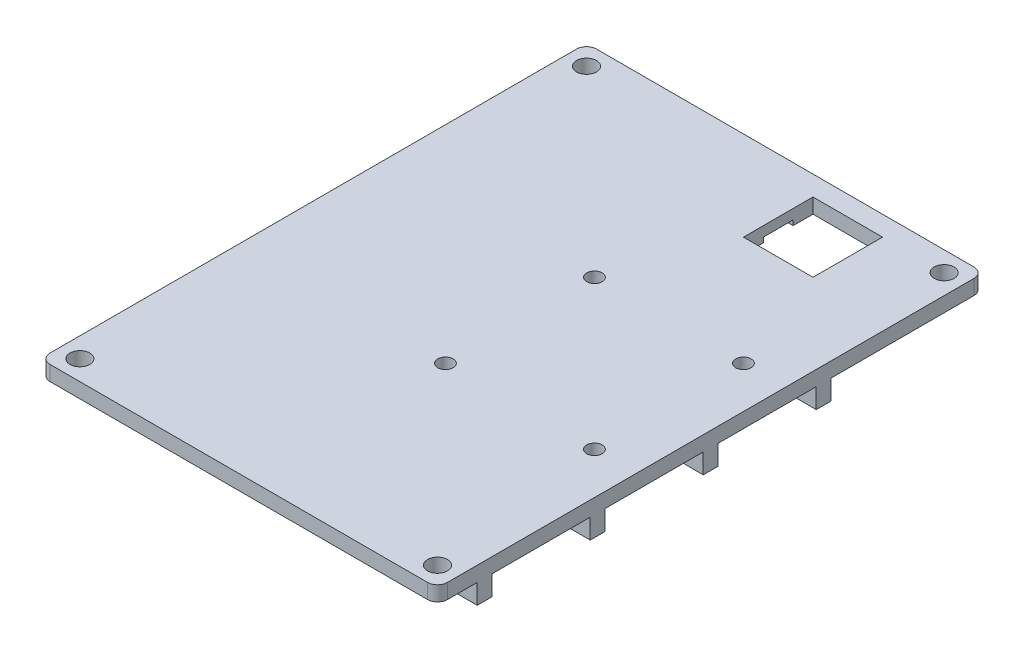
SolidWorks part; units mm, degrees
ref_plane "前视基准面" through (0, 0, 0) normal (0, 0, 1) x (1, 0, 0)
ref_plane "上视基准面" through (0, 0, 0) normal (0, 1, 0) x (1, 0, 0)
ref_plane "右视基准面" through (0, 0, 0) normal (1, 0, 0) x (0, 0, -1)
other "Configuration Table"
sketch "草图1" plane through (0, 0, 0) normal (0, 1, 0) x (1, 0, 0)
  line L0 (-40, -6) -> (0, -6)
  line L9 (-36, 6) -> (0, 6)
  line L10 (0, 6) -> (40, 6)
  line L11 (40, 6) -> (40, 0)
  line L12 (0, -6) -> (40, -6)
  line L13 (40, -6) -> (40, 0)
  line L17 (-36, 6) -> (-40, 6)
  line L18 (-40, 6) -> (-40, -6)
extrude "凸台-拉伸1" add sketch "草图1" along normal blind 12 contours L9 L10 L11 L13 L12 L0 L18 L17
sketch "草图2" plane through (0, 0, 6) normal (0, 0, 1) x (1, 0, 0)
  line L0 (0, 0) -> (-36, 0)
  line L1 (-40, 0) -> (40, 0) construction
  line L2 (0, 0) -> (36, 0)
  line L3 (-40, 0) -> (-40, 4)
  line L4 (-40, 12) -> (-40, 0) construction
  line L5 (-40, 4) -> (-32, 4)
  line L6 (-32, 4) -> (-32, 12)
  line L7 (-40, 12) -> (40, 12) construction
  line L8 (40, 0) -> (40, 4)
  line L9 (40, 12) -> (40, 0) construction
  line L10 (40, 4) -> (32, 4)
  line L11 (32, 4) -> (32, 12)
  line L12 (-32, 4) -> (-32, 8)
  line L13 (-32, 8) -> (32, 8)
  line L14 (-32, 4) -> (-28, 4)
  line L15 (32, 4) -> (28, 4)
  line L16 (-28, 4) -> (-28, 0)
  line L17 (-28, 4) -> (-28, 8)
  line L18 (28, 4) -> (28, 0)
  line L19 (28, 4) -> (28, 8)
  line L20 (28, 8) -> (-28, 8)
  line L21 (-28, 0) -> (28, 0)
  line M9 (-40, 0) -> (40, 0)
  line M10 (40, 0) -> (40, 12)
  line M11 (40, 12) -> (-40, 12)
  line M12 (-40, 12) -> (-40, 0)
extrude "切除-拉伸1" cut sketch "草图2" against normal blind 12 contours L18 L19 L13 L17 L16 L0 M9 | L5 L6 M11 M12 | L11 L10 M10 M11
sketch "草图3" plane through (0, 12, 0) normal (0, 1, 0) x (1, 0, 0)
  line L0 (40, 6) -> (40, 4)
  line L1 (40, 6) -> (40, -6) construction
  line L4 (38, 6) -> (40, 6)
  line L5 (-40, 6) -> (-38, 6)
  line L6 (-40, 6) -> (-32, 6) construction
  line L8 (-40, 6) -> (-40, -6) construction
  line L9 (-40, 6) -> (-40, 4)
  circle A0 centre (-36, 2) radius 2
  circle A1 centre (36, 2) radius 2
  arc A2 (40, 4) -> (38, 6) centre (38, 4) ccw
  arc A3 (-40, 4) -> (-38, 6) centre (-38, 4) cw
extrude "切除-拉伸2" cut sketch "草图3" against normal blind 12 contours L9 A3 L5 | A0 | A2 L0 L4 | A1
sketch "草图4" plane through (0, 12, 0) normal (0, 1, 0) x (1, 0, 0)
  line L0 (-21.1, 0) -> (-21.1, 6)
  line L1 (-12.1, 0) -> (12.08, 0)
  line L2 (-21.1, 6) -> (-16.6, 6)
  line L3 (32, 6) -> (-32, 6) construction
  line L5 (-32, -6) -> (32, -6) construction
  line L6 (12.08, -1) -> (12.08, -6)
  line L7 (-12.1, 6) -> (12.08, 6)
  line L8 (-21.1, 0) -> (-21.1, -6)
  line L9 (-21.1, -6) -> (-16.6, -6)
  line L10 (-12.1, 0) -> (-12.1, -6)
  line L11 (-12.1, -6) -> (-16.6, -6)
  line L13 (-12.1, 6) -> (-16.6, 6)
  line L14 (12.08, 0) -> (12.08, -1)
  line L18 (12.08, -6) -> (16.6, -6)
  line L20 (12.08, 6) -> (16.6, 6)
  line L21 (21.12, -1) -> (21.12, 6)
  line L22 (21.12, 6) -> (16.6, 6)
  line L23 (21.12, -1) -> (21.12, -6)
  line L24 (21.12, -6) -> (16.6, -6)
extrude "切除-拉伸3" cut sketch "草图4" against normal blind 1 contours L0 L2 L13 L7 L20 L22 L21 L23 L24 L18 L6 L14 L1 L10 L11 L9 L8
sketch "草图5" plane through (0, 12, 0) normal (0, 1, 0) x (1, 0, 0)
  line L0 (-36, 2) -> (-36, -2)
  line L1 (-36, -2) -> (40, -2)
  line L2 (40, 4) -> (40, -6) construction
  line L3 (40, -2) -> (-40, -2)
  line L4 (-40, 4) -> (-40, -6) construction
  line L5 (-40, -2) -> (-40, -6)
  line L6 (-40, -6) -> (40, -6)
  line L7 (40, -6) -> (40, -2)
extrude "切除-拉伸4" cut sketch "草图5" against normal blind 20
sketch "草图6" plane through (0, 12, 0) normal (0, 1, 0) x (1, 0, 0)
  line L0 (12.08, 0) -> (12.08, 6)
  line L1 (21.12, 6) -> (-21.1, 6) construction
  line L2 (12.08, 6) -> (-21.1, 6)
  line L3 (-21.1, 6) -> (-21.1, -2)
  line L4 (-21.1, -2) -> (-12.1, -2)
  line L5 (-21.1, -2) -> (-12.1, -2) construction
  line L6 (-12.1, -2) -> (-12.1, 0)
  line L7 (-12.1, 0) -> (12.08, 0)
extrude "凸台-拉伸2" add sketch "草图6" against normal blind 1
sketch "草图7" plane through (0, 12, 0) normal (0, 1, 0) x (1, 0, 0)
  line L0 (21.12, -2) -> (32, -2) construction
  line L1 (21.12, 6) -> (21.32, 6)
  line L2 (21.12, 6) -> (21.12, -2)
  line L3 (21.12, -2) -> (21.32, -2)
  line L4 (21.32, 6) -> (21.32, -2)
  line L5 (-32, -2) -> (12.08, -2) construction
  line L6 (12.08, 6) -> (11.88, 6)
  line L7 (12.08, 6) -> (12.08, -2)
  line L8 (12.08, -2) -> (11.88, -2)
  line L9 (11.88, 6) -> (11.88, -2)
extrude "切除-拉伸5" cut sketch "草图7" against normal blind 1
sketch "草图8" plane through (0, 12, 0) normal (0, 1, 0) x (1, 0, 0)
  line L0 (-32, -2) -> (-40, -2)
  line L1 (-40, -2) -> (-40, 4)
  line L4 (-38, 6) -> (-32, 6)
  line L5 (-32, 6) -> (-32, -2)
  line L6 (32, -2) -> (40, -2)
  line L7 (40, -2) -> (40, 4)
  line L10 (38, 6) -> (32, 6)
  line L11 (32, 6) -> (32, -2)
  arc A0 (-38, 6) -> (-40, 4) centre (-38, 4) ccw construction
  arc A1 (-40, 4) -> (-38, 6) centre (-38, 4) cw
  arc A2 (40, 4) -> (38, 6) centre (38, 4) ccw
  circle A3 centre (-36, 2) radius 2
  circle A4 centre (36, 2) radius 2
  line M17 (-32, 6) -> (-32, -2)
extrude "凸台-拉伸3" add sketch "草图8" against normal blind 4 contours A4 | A1 L1 L0 L4 A3 M17 | L10 L11 L6 L7 A2
sketch "草图9" plane through (0, 0, 2) normal (0, 0, 1) x (1, 0, 0)
  line L0 (40, 8) -> (40, 12) construction
  line L1 (-40, 0) -> (40, 0)
  line L2 (-40, 0) -> (-40, 9)
  line L3 (-40, 9) -> (40, 9)
  line L4 (40, 0) -> (40, 9)
extrude "切除-拉伸6" cut sketch "草图9" against normal blind 14
sketch "草图10" plane through (0, 0, -6) normal (0, 0, -1) x (-1, 0, 0)
  line L0 (-21.32, 11) -> (-21.32, 9)
  line L1 (38, 9) -> (-38, 9) construction
  line L2 (-11.88, 11) -> (-11.88, 9)
  line L3 (-11.88, 10) -> (-21.32, 10)
  line L4 (-21.32, 9) -> (-11.88, 9)
  line L5 (-21.32, 10) -> (-21.32, 9)
  line L6 (-11.88, 10) -> (-11.88, 9)
  line M1 (-38, 9) -> (38, 9)
extrude "切除-拉伸7" cut sketch "草图10" against normal blind 14 contours L2 L3 L0 M1
sketch "草图11" plane through (0, 0, -6) normal (0, 0, -1) x (-1, 0, 0)
  line L1 (-21.32, 11) -> (-11.88, 11)
  line L2 (-21.32, 11) -> (-21.32, 12)
  line L3 (-21.32, 12) -> (-11.88, 12)
  line L4 (-11.88, 11) -> (-11.88, 12)
extrude "凸台-拉伸4" add sketch "草图11" against normal blind 8 contours L2 L1 L4 L3
sketch "草图12" plane through (0, 9, 0) normal (0, -1, 0) x (1, 0, 0)
  line L0 (11.88, 2) -> (21.32, 2)
  line L1 (21.32, 2) -> (21.32, -7.44)
  line L2 (21.32, -7.44) -> (11.88, -7.44)
  line L3 (11.88, 2) -> (11.88, -7.44)
  line L4 (11.88, 2) -> (21.32, -7.44)
  circle A0 centre (16.6, -2.72) radius 4.45
extrude "切除-拉伸8" cut sketch "草图12" against normal blind 8 contours L4 A0 | L4 A0
sketch "草图13" plane through (0, 12, 0) normal (0, 1, 0) x (1, 0, 0)
  line L1 (-40, -2) -> (40, -2)
  line L2 (-40, -2) -> (-40, -5)
  line L3 (-40, -5) -> (40, -5)
  line L4 (40, -2) -> (40, -5)
extrude "凸台-拉伸5" add sketch "草图13" against normal blind 7 contours L2 L1 L4 L3
sketch "草图14" plane through (0, 12, 0) normal (0, 1, 0) x (1, 0, 0)
  line L7 (-40, -100) -> (-40, -5)
  line L8 (-40, -5) -> (40, -5)
  line L9 (-40, -5) -> (40, -5) construction
  line L10 (40, -5) -> (40, -100)
  line L11 (-40, -100) -> (-40, -102)
  line L12 (-38, -104) -> (-36, -104)
  line L13 (36, -104) -> (38, -104)
  line L15 (-36, -104) -> (36, -104)
  line L17 (40, -102) -> (40, -100)
  arc A0 (-40, -102) -> (-38, -104) centre (-38, -102) ccw
  circle A1 centre (-36, -100) radius 1.6
  arc A2 (38, -104) -> (40, -102) centre (38, -102) ccw
  circle A3 centre (36, -100) radius 1.6
extrude "凸台-拉伸7" add sketch "草图14" against normal blind 3 contours A1 | A3 | L11 A0 L12 L15 L13 A2 L17 L10 L8 L7
sketch "草图16" plane through (-40, 0, 0) normal (-1, 0, 0) x (0, 0, 1)
  line L0 (104, 9) -> (96, 9)
  line L1 (102, 9) -> (5, 9) construction
  line L2 (96, 5) -> (96, 9)
  line L3 (96, 5) -> (93, 5)
  line L4 (93, 5) -> (93, 9)
  line L5 (93, 9) -> (96, 9)
extrude "凸台-拉伸8" add sketch "草图16" against normal blind 80 contours L2 L3 L4 L5
sketch "草图17" plane through (0, 12, 0) normal (0, 1, 0) x (1, 0, 0)
  line L0 (13.5927, 6) -> (19.6073, 6)
  line L1 (19.6073, 6) -> (16.6, 2.72)
  line L2 (16.6, -49) -> (31.6, -49)
  line L3 (-36, 2) -> (36, -100)
  line L4 (16.6, -49) -> (1.6, -49)
  line L5 (16.6, -49) -> (16.6, 2.72)
  line L6 (1.6, -49) -> (1.6, -34)
  line L7 (1.6, -49) -> (1.6, -64)
  line L8 (31.6, -49) -> (31.6, -64)
  line L9 (31.6, -49) -> (31.6, -34)
  circle A0 centre (1.6, -34) radius 1.55
  circle A1 centre (31.6, -34) radius 1.55
  circle A2 centre (31.6, -64) radius 1.55
  circle A3 centre (1.6, -64) radius 1.55
extrude "切除-拉伸11" cut sketch "草图17" against normal blind 7
sketch "草图21" plane through (0, 12, 0) normal (0, 1, 0) x (1, 0, 0)
  circle A0 centre (-36, -100) radius 2
  circle A1 centre (36, -100) radius 2
extrude "切除-拉伸12" cut sketch "草图21" against normal blind 7 contours A1 | A0
sketch "草图22" plane through (0, 9, 0) normal (0, -1, 0) x (-1, 0, 0)
  line L1 (40, -93) -> (40, -5) construction
  line L2 (-40, -5) -> (-40, -93) construction
  line L3 (40, -49) -> (40, -50.5)
  line L4 (40, -49) -> (40, -47.5)
  line L5 (40, -50.5) -> (-40, -50.5)
  line L6 (-40, -50.5) -> (-40, -49)
  line L7 (40, -47.5) -> (-40, -47.5)
  line L8 (-40, -47.5) -> (-40, -49)
  line L9 (40, -50.5) -> (40, -93)
  line L11 (40, -26.25) -> (40, -27.75)
  line L12 (40, -26.25) -> (40, -24.75)
  line L13 (40, -27.75) -> (-40, -27.75)
  line L14 (40, -24.75) -> (-40, -24.75)
  line L15 (-40, -24.75) -> (-40, -27.75)
  line L16 (-40, -71.75) -> (-40, -73.25)
  line L17 (-40, -71.75) -> (-40, -70.25)
  line L18 (-40, -73.25) -> (40, -73.25)
  line L19 (-40, -70.25) -> (40, -70.25)
  line L20 (40, -70.25) -> (40, -73.25)
extrude "凸台-拉伸9" add sketch "草图22" along normal blind 4 contours L17 L19 L20 L18 L16 | L3 L4 L7 L8 L6 L5 | L14 L15 L13 L11 L12
sketch "草图23" plane through (-40, 0, 0) normal (-1, 0, 0) x (0, 0, 1)
  line L1 (2, 5) -> (5, 5)
  line L2 (2, 5) -> (2, 9)
  line L3 (2, 9) -> (5, 9)
  line L4 (5, 5) -> (5, 9)
  line M7 (2, 9) -> (2, 5)
  line M8 (2, 5) -> (5, 5)
  line M9 (5, 5) -> (5, 9)
extrude "切除-拉伸13" cut sketch "草图23" against normal blind 200 contours L3 M7 M8 M9
sketch "草图24" plane through (0, 9, 0) normal (0, -1, 0) x (1, 0, 0)
  line L0 (11.88, 2) -> (21.32, -6)
  line L1 (16.6, -2) -> (16.6, -6)
  line L2 (16.6, -2) -> (16.6, 12)
  line L3 (16.6, 12) -> (23.6, 12)
  line L4 (16.6, 12) -> (9.6, 12)
  line L5 (16.6, -2) -> (23.6, -2)
  line L6 (23.6, -2) -> (23.6, 12)
  line L7 (16.6, -2) -> (9.6, -2)
  line L8 (9.6, -2) -> (9.6, 12)
  line M9 (11.88, -6) -> (11.88, 2)
  line M10 (11.88, 2) -> (21.32, 2)
  line M11 (21.32, 2) -> (21.32, -6)
extrude "切除-拉伸15" cut sketch "草图24" against normal blind 5 contours L8 L7 L2 L4 M9 M10 | L5 L6 L3 L2 M10 M11
sketch "草图25" plane through (0, 10, 0) normal (0, -1, 0) x (-1, 0, 0)
  line L1 (-11.88, -2) -> (-21.32, -2)
  line L2 (-11.88, -2) -> (-11.88, 2)
  line L3 (-11.88, 2) -> (-21.32, 2)
  line L4 (-21.32, -2) -> (-21.32, 2)
extrude "切除-拉伸16" cut sketch "草图25" against normal blind 5 contours L2 L1 L4 L3
sketch "草图26" plane through (0, 10, 0) normal (0, -1, 0) x (-1, 0, 0)
  line L1 (-11.88, 6) -> (-21.32, 6)
  line L2 (-11.88, 6) -> (-11.88, 2)
  line L3 (-11.88, 2) -> (-21.32, 2)
  line L4 (-21.32, 6) -> (-21.32, 2)
extrude "凸台-拉伸10" add sketch "草图26" against normal blind 2 contours L2 L1 L4 L3
sketch "草图27" plane through (0, 10, 0) normal (0, -1, 0) x (1, 0, 0)
  line L1 (11.88, -6) -> (21.32, -6)
  line L2 (11.88, -6) -> (11.88, -2)
  line L3 (11.88, -2) -> (21.32, -2)
  line L4 (21.32, -6) -> (21.32, -2)
extrude "凸台-拉伸11" add sketch "草图27" along normal blind 1 contours L2 L1 L4 L3
sketch "草图28" plane through (0, 9, 0) normal (0, -1, 0) x (1, 0, 0)
  line L1 (23.6, 12) -> (28.6, 12)
  line L2 (23.6, 12) -> (23.6, -2)
  line L3 (23.6, -2) -> (28.6, -2)
  line L4 (28.6, 12) -> (28.6, -2)
  line L5 (9.6, 12) -> (4.6, 12)
  line L6 (9.6, 12) -> (9.6, -2)
  line L7 (9.6, -2) -> (4.6, -2)
  line L8 (4.6, 12) -> (4.6, -2)
  line M15 (23.6, 12) -> (23.6, -2)
  line M17 (9.6, -2) -> (9.6, 12)
extrude "切除-拉伸17" cut sketch "草图28" against normal blind 1 contours L5 L8 L7 M17 | L4 L1 L3 M15
sketch "草图29" plane through (0, 10, 0) normal (0, -1, 0) x (1, 0, 0)
  line L0 (9.6, -2) -> (9.6, 12) construction
  line L1 (4.6, 12) -> (9.6, 12)
  line L2 (4.6, 12) -> (4.6, 8)
  line L3 (4.6, 8) -> (9.6, 8)
  line L4 (9.6, 12) -> (9.6, 8)
  line L5 (23.6, 12) -> (23.6, -2) construction
  line L6 (28.6, 12) -> (23.6, 12)
  line L7 (28.6, 12) -> (28.6, 8)
  line L8 (28.6, 8) -> (23.6, 8)
  line L9 (23.6, 12) -> (23.6, 8)
  line L11 (4.6, -2) -> (9.6, -2)
  line L12 (4.6, -2) -> (4.6, 2)
  line L13 (4.6, 2) -> (9.6, 2)
  line L14 (9.6, -2) -> (9.6, 2)
  line L15 (28.6, -2) -> (23.6, -2)
  line L16 (28.6, -2) -> (28.6, 2)
  line L17 (28.6, 2) -> (23.6, 2)
  line L18 (23.6, -2) -> (23.6, 2)
  line M11 (28.6, -2) -> (28.6, 12)
  line M12 (28.6, 12) -> (23.6, 12)
  line M13 (23.6, 12) -> (23.6, -2)
  line M14 (23.6, -2) -> (28.6, -2)
extrude "凸台-拉伸12" add sketch "草图29" along normal blind 1 contours L11 L14 L13 L12 | L8 M11 M12 M13 | L17 M11 M13 M14 | L2 L1 L4 L3
